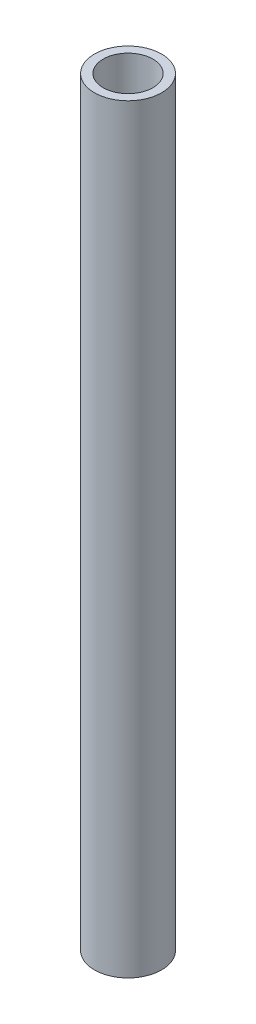
SolidWorks part; units mm, degrees
material "PVC Rigid"
ref_plane "Front Plane" through (0, 0, 0) normal (0, 0, 1) x (1, 0, 0)
ref_plane "Top Plane" through (0, 0, 0) normal (0, 1, 0) x (1, 0, 0)
ref_plane "Right Plane" through (0, 0, 0) normal (1, 0, 0) x (0, 0, -1)
sketch "Sketch1" plane through (0, 0, 0) normal (0, 1, 0) x (1, 0, 0)
  circle A0 centre (0, 0) radius 10.668
  circle A1 centre (0, 0) radius 7.8994
  dimension "D1" = 21.336
  dimension "D2" = 15.7988
  dimension "D3" = 2.7686
extrude "Boss-Extrude1" add sketch "Sketch1" along normal blind 241.3
